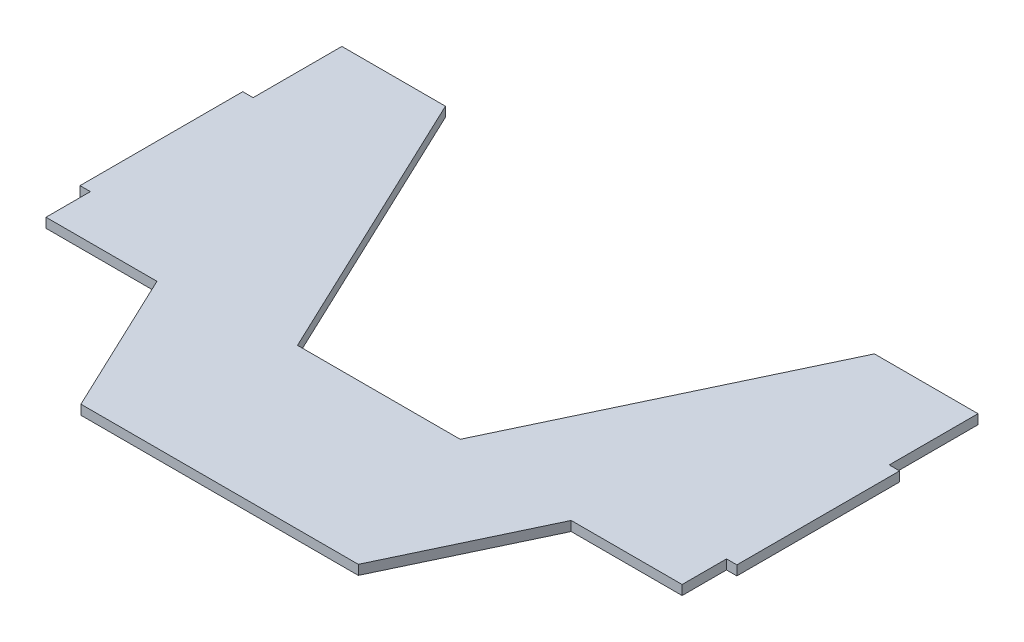
SolidWorks part; units mm, degrees
ref_plane "Front Plane" through (0, 0, 0) normal (0, 0, 1) x (1, 0, 0)
ref_plane "Top Plane" through (0, 0, 0) normal (0, 1, 0) x (1, 0, 0)
ref_plane "Right Plane" through (0, 0, 0) normal (1, 0, 0) x (0, 0, -1)
sketch "Sketch1" plane through (0, 0, 0) normal (0, 1, 0) x (1, 0, 0)
  line L1 (-43, 20) -> (43, 20)
  line L2 (-43, 20) -> (-43, -20)
  line L3 (-43, -20) -> (43, -20)
  line L4 (43, 20) -> (43, -20)
  line L5 (-43, 20) -> (43, -20) construction
  line L6 (-43, -20) -> (43, 20) construction
  point P0 (0, 0)
  dimension "D1" = 86
  dimension "D2" = 40
extrude "Boss-Extrude1" add sketch "Sketch1" along normal blind 1.3
sketch "Sketch2" plane through (0, 1.3, 0) normal (0, 1, 0) x (1, 0, 0)
  line L0 (-43, 20) -> (-43, -20) construction
  line L1 (-43, 8) -> (-44.4, 8)
  line L2 (-43, 8) -> (-43, -14)
  line L3 (-43, -14) -> (-44.4, -14)
  line L4 (-44.4, 8) -> (-44.4, -14)
  line L5 (43, -20) -> (43, 20) construction
  line L6 (43, 8) -> (44.4, 8)
  line L7 (43, 8) -> (43, -14)
  line L8 (43, -14) -> (44.4, -14)
  line L9 (44.4, 8) -> (44.4, -14)
  line L10 (43, 20) -> (-43, 20) construction
  dimension "D1" = 1.4
  dimension "D2" = 1.4
  dimension "D3" = 22
  dimension "D4" = 22
  dimension "D5" = 12
  dimension "D6" = 12
extrude "Boss-Extrude2" add sketch "Sketch2" against normal blind 1.3
sketch "Sketch3" plane through (0, 1.3, 0) normal (0, 1, 0) x (1, 0, 0)
  line L0 (-43, 20) -> (-29, 20)
  line L1 (43, 20) -> (-43, 20) construction
  line L2 (-29, 20) -> (-11, -18)
  line L4 (-11, -18) -> (11, -18)
  line L5 (11, -18) -> (29, 20)
  line L6 (29, 20) -> (43, 20)
  line L7 (-29, 20) -> (29, 20)
  line M9 (43, 20) -> (-43, 20)
  dimension "D1" = 14
  dimension "D2" = 14
  dimension "D3" = 22
  dimension "D4" = 18
  dimension "D5" = 18
  dimension "D6" = 38
extrude "Cut-Extrude1" cut sketch "Sketch3" against normal through all contours L4 L5 L2 M9
sketch "Sketch4" plane through (0, 0, 0) normal (0, 1, 0) x (1, 0, 0)
  line L0 (-28, -20) -> (-18.75, -39.5278)
  line L1 (-43, -20) -> (43, -20) construction
  line L2 (-18.75, -39.5278) -> (18.75, -39.5278)
  line L3 (18.75, -39.5278) -> (28, -20)
  line L4 (11, -18) -> (29, 20) construction
  line L5 (-29, 20) -> (-11, -18) construction
  line L6 (0, -0.715) -> (0, 0.715) construction
  line L7 (-28, -20) -> (28, -20)
  dimension "D1" = 28
  dimension "D2" = 28
  dimension "D3" = 37.5
extrude "Boss-Extrude3" add sketch "Sketch4" along normal blind 1.3
